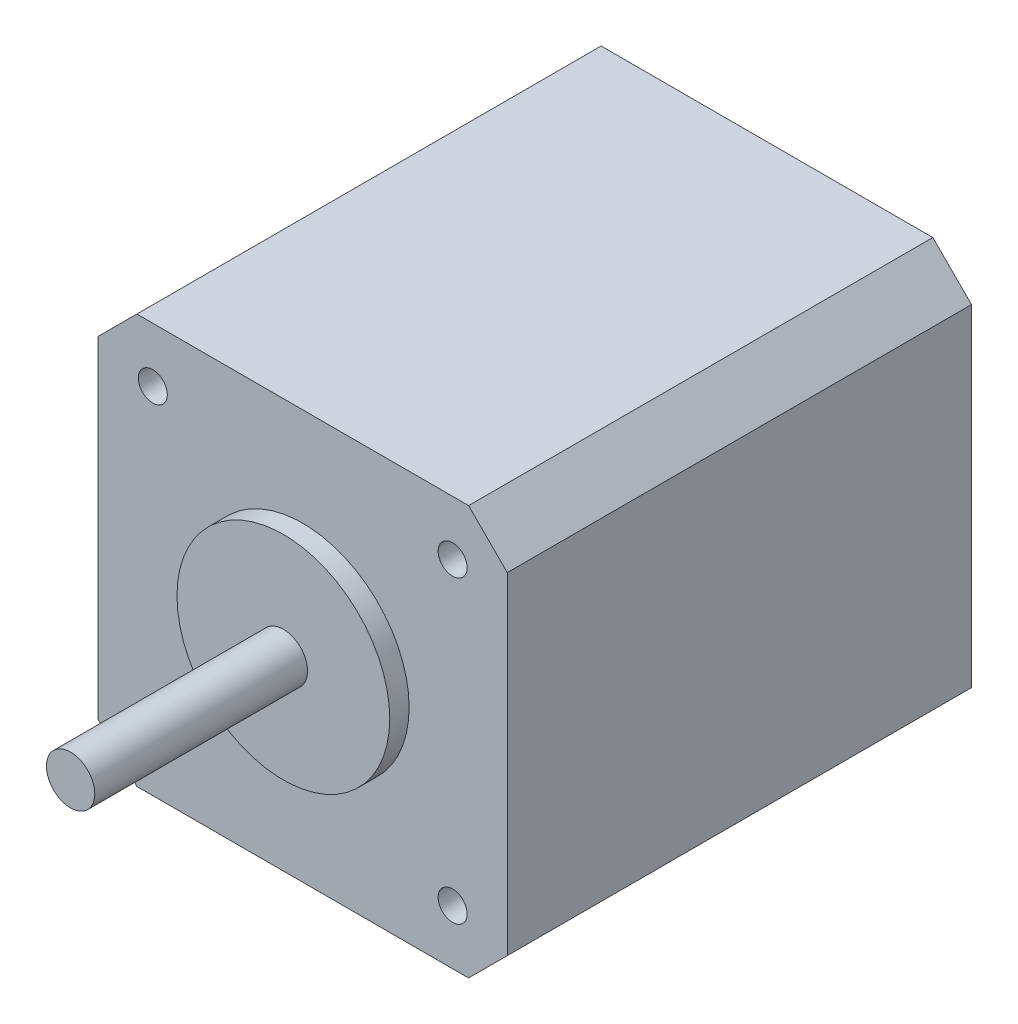
SolidWorks part; units mm, degrees
ref_plane "Front Plane" through (0, 0, 0) normal (0, 0, 1) x (1, 0, 0)
ref_plane "Top Plane" through (0, 0, 0) normal (0, 1, 0) x (1, 0, 0)
ref_plane "Right Plane" through (0, 0, 0) normal (1, 0, 0) x (0, 0, -1)
sketch "Sketch1" plane through (0, 0, 0) normal (0, 0, 1) x (1, 0, 0)
  line L1 (-21.15, 21.15) -> (21.15, 21.15)
  line L2 (-21.15, 21.15) -> (-21.15, -21.15)
  line L3 (-21.15, -21.15) -> (21.15, -21.15)
  line L4 (21.15, 21.15) -> (21.15, -21.15)
  line L5 (-21.15, 21.15) -> (21.15, -21.15) construction
  line L6 (-21.15, -21.15) -> (21.15, 21.15) construction
  point P0 (0, 0)
  dimension "D1" = 42.3
extrude "Boss-Extrude1" add sketch "Sketch1" against normal blind 48
sketch "Sketch2" plane through (0, 0, 0) normal (0, 0, 1) x (1, 0, 0)
  line L1 (-15.5, 15.5) -> (15.5, 15.5) construction
  line L2 (-15.5, 15.5) -> (-15.5, -15.5) construction
  line L3 (-15.5, -15.5) -> (15.5, -15.5) construction
  line L4 (15.5, 15.5) -> (15.5, -15.5) construction
  line L5 (-15.5, 15.5) -> (15.5, -15.5) construction
  line L6 (-15.5, -15.5) -> (15.5, 15.5) construction
  circle A0 centre (-15.5, 15.5) radius 1.5
  circle A1 centre (15.5, 15.5) radius 1.5
  circle A2 centre (15.5, -15.5) radius 1.5
  circle A3 centre (-15.5, -15.5) radius 1.5
  point P0 (0, 0)
  dimension "D2" = 3
  dimension "D1" = 31
extrude "Cut-Extrude1" cut sketch "Sketch2" against normal blind 6
sketch "Sketch3" plane through (0, 0, 0) normal (0, 0, 1) x (1, 0, 0)
  circle A0 centre (0, 0) radius 11
  dimension "D1" = 22
extrude "Boss-Extrude2" add sketch "Sketch3" along normal blind 2
sketch "Sketch4" plane through (0, 0, 2) normal (0, 0, 1) x (1, 0, 0)
  circle A0 centre (0, 0) radius 2.5
  dimension "D1" = 5
extrude "Boss-Extrude3" add sketch "Sketch4" along normal offset from surface (22 mm away) 24 up to face at (11, 0, 0) offset beyond the face yes
chamfer "Chamfer1" distance 4 angle 45 4 edges at (-21.15, -21.15, -24) (21.15, -21.15, -24) (21.15, 21.15, -24) (-21.15, 21.15, -24)
